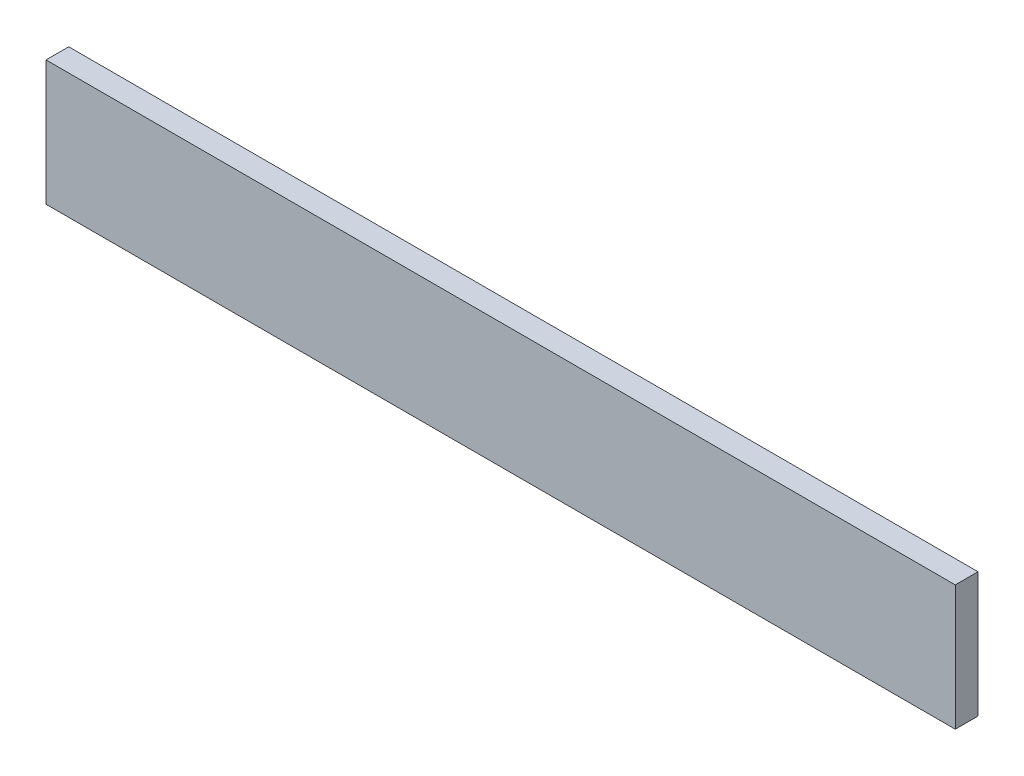
SolidWorks part; units mm, degrees
material "Plywood"
ref_plane "Plan de face" through (0, 0, 0) normal (0, 0, 1) x (1, 0, 0)
ref_plane "Plan de dessus" through (0, 0, 0) normal (0, 1, 0) x (1, 0, 0)
ref_plane "Plan de droite" through (0, 0, 0) normal (1, 0, 0) x (0, 0, -1)
sketch "Esquisse1" plane through (0, 0, 0) normal (0, 0, 1) x (1, 0, 0)
  line L1 (0, 0) -> (80, 0)
  line L2 (0, 0) -> (0, 11)
  line L3 (0, 11) -> (80, 11)
  line L4 (80, 0) -> (80, 11)
  dimension "D1" = 11
  dimension "D2" = 80
extrude "Boss.-Extru.1" add sketch "Esquisse1" along normal blind 2
